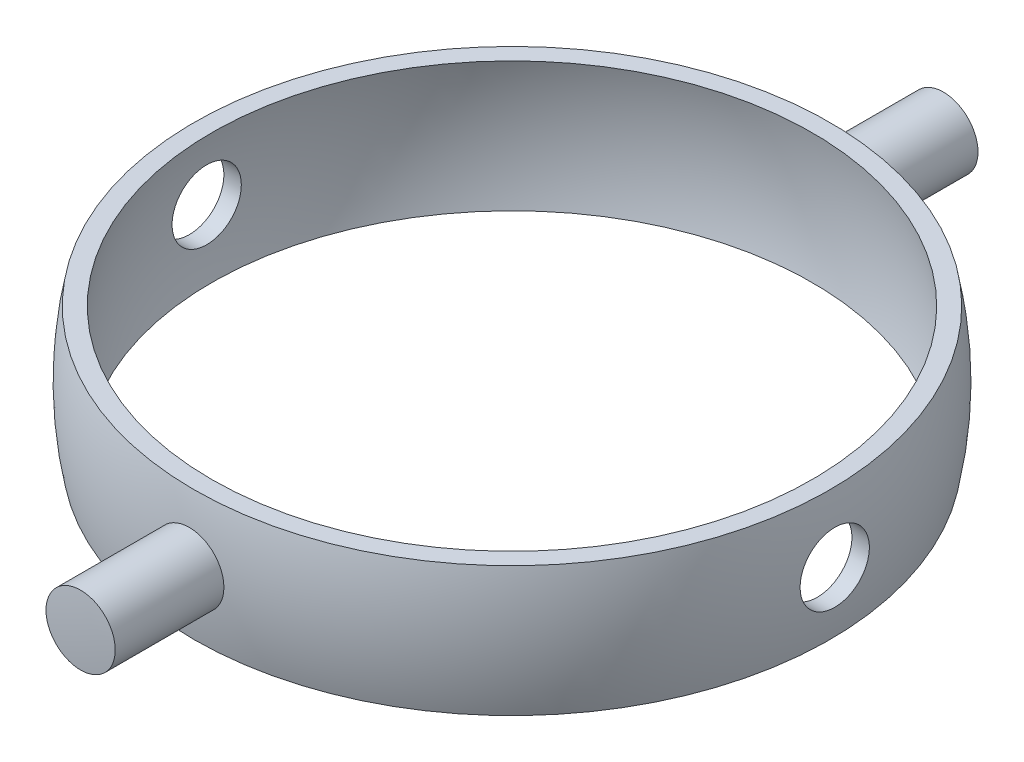
SolidWorks part; units mm, degrees
ref_plane "Front Plane" through (0, 0, 0) normal (0, 0, 1) x (1, 0, 0)
ref_plane "Top Plane" through (0, 0, 0) normal (0, 1, 0) x (1, 0, 0)
ref_plane "Right Plane" through (0, 0, 0) normal (1, 0, 0) x (0, 0, -1)
sketch "Sketch1" plane through (0, 0, 0) normal (0, 0, 1) x (1, 0, 0)
  line L0 (0, 11.2479) -> (0, 0) construction
  line L1 (0, 0) -> (-39.2165, 0) construction
  line L2 (-36.7423, 7.5) -> (-34.6987, 7.5)
  line L3 (-36.7423, -7.5) -> (-34.6987, -7.5)
  arc A0 (-36.7423, 7.5) -> (-36.7423, -7.5) centre (0, 0) ccw
  arc A1 (-34.6987, 7.5) -> (-34.6987, -7.5) centre (0, 0) ccw
  dimension "D1" = 37.5
  dimension "D2" = 35.5
  dimension "D3" = 15
revolve "Revolve1" add sketch "Sketch1" angle 360 about L0
sketch "Sketch2" plane through (0, 0, 0) normal (1, 0, 0) x (0, 0, -1)
  circle A0 centre (0, 0) radius 4
  dimension "D1" = 8
extrude "Cut-Extrude1" cut sketch "Sketch2" against normal through all both and the other way through all
ref_plane "Plane1" through (0, 0, 50) normal (0, 0, 1) x (1, 0, 0)
sketch "Sketch3" plane through (0, 0, 50) normal (0, 0, 1) x (1, 0, 0)
  circle A0 centre (0, 0) radius 4
  dimension "D1" = 8
extrude "Boss-Extrude1" add sketch "Sketch3" against normal up to surface (12.7139 mm away)
mirror "Mirror1" about plane through (0, 0, 0) normal (0, 0, 1) of "Boss-Extrude1"
sketch "Sketch4" plane through (0, 0, 0) normal (1, 0, 0) x (0, 0, -1)
  line L0 (0, 23.2253) -> (0, 0) construction
  line L1 (0, 0) -> (-50, 0) construction
  line L2 (-50, 4) -> (-50, -4) construction
  line L3 (0, 55) -> (0, 50)
  line L4 (0, -50) -> (0, -55)
  arc A0 (-48.8459, 25.2799) -> (-46.6399, -29.1499) centre (0, 0) ccw
  arc A1 (-44.782, 22.239) -> (-42.3091, -26.6447) centre (0, 0) ccw
  arc A2 (-48.8459, 25.2799) -> (0, 55) centre (0, 0) cw
  arc A3 (-44.782, 22.239) -> (0, 50) centre (0, 0) cw
  arc A4 (-42.3091, -26.6447) -> (0, -50) centre (0, 0) ccw
  arc A5 (-46.6399, -29.1499) -> (0, -55) centre (0, 0) ccw
  dimension "D1" = 50
  dimension "D2" = 55
revolve "Cut-Revolve1" cut sketch "Sketch4" angle 360 about L0
